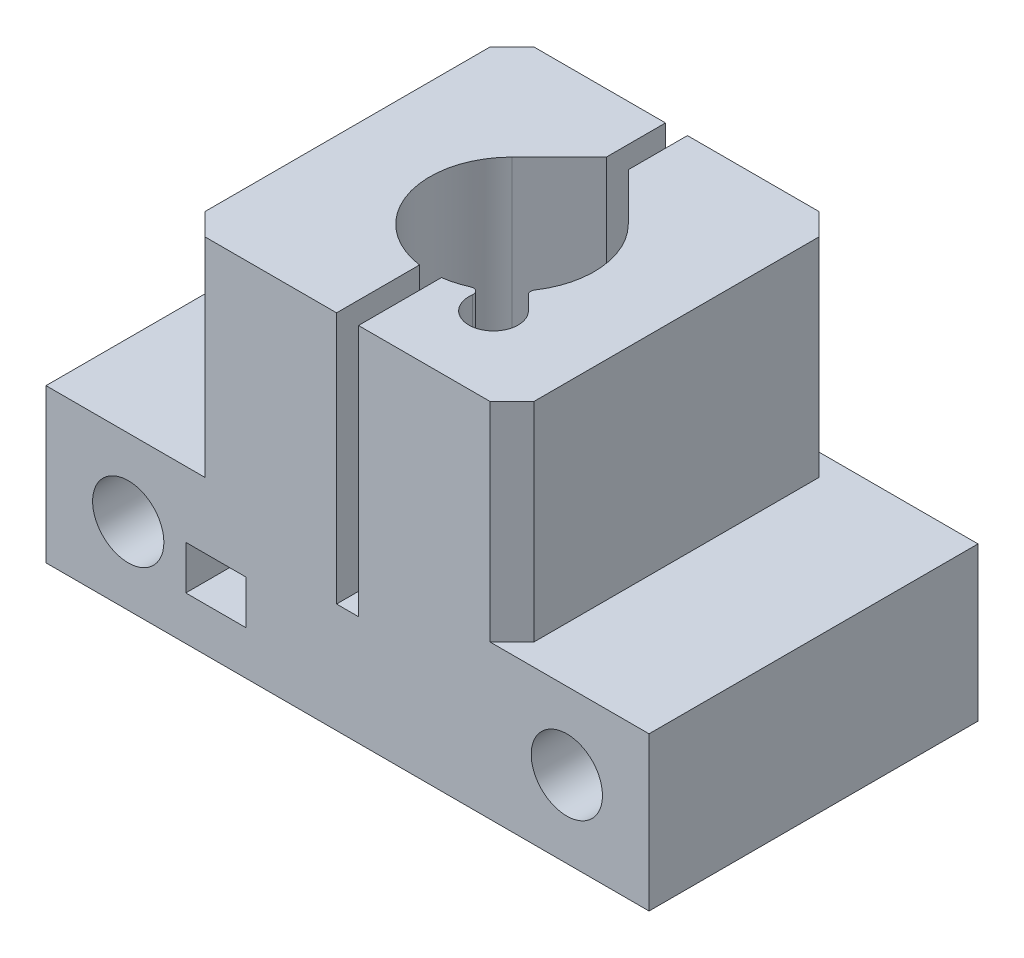
SolidWorks part; units mm, degrees
material "Printed PLA"
ref_plane "Front Plane" through (0, 0, 0) normal (0, 0, 1) x (1, 0, 0)
ref_plane "Top Plane" through (0, 0, 0) normal (0, 1, 0) x (1, 0, 0)
ref_plane "Right Plane" through (0, 0, 0) normal (1, 0, 0) x (0, 0, -1)
sketch "Sketch1" plane through (0, 0, 0) normal (0, 0, 1) x (1, 0, 0)
  line L0 (-27.5, 0) -> (27.5, 0)
  line L1 (27.5, 0) -> (27.5, 14)
  line L2 (27.5, 14) -> (15, 14)
  line L3 (15, 14) -> (15, 33)
  line L4 (15, 33) -> (1, 33)
  line L5 (1, 33) -> (1, 10)
  line L6 (1, 10) -> (-1, 10)
  line L7 (-1, 10) -> (-1, 33)
  line L8 (-1, 33) -> (-15, 33)
  line L9 (-15, 33) -> (-15, 14)
  line L10 (-15, 14) -> (-27.5, 14)
  line L11 (-27.5, 14) -> (-27.5, 0)
  line L12 (0, 10) -> (0, 0) construction
  line L13 (-27.5, 7) -> (-20, 7) construction
  line L14 (-20, 7) -> (20, 7) construction
  line L15 (20, 7) -> (27.5, 7) construction
  circle A0 centre (-20, 7) radius 3.25
  circle A1 centre (20, 7) radius 3.25
  dimension "D8" = 6.5
  dimension "D1" = 2
  dimension "D2" = 30
  dimension "D3" = 10
  dimension "D4" = 33
  dimension "D5" = 55
  dimension "D6" = 14
  dimension "D7" = 40
extrude "Boss-Extrude1" add sketch "Sketch1" along normal mid plane 30
sketch "Sketch2" plane through (0, 33, 0) normal (0, 1, 0) x (1, 0, 0)
  line L0 (-3.5355, 3.5355) -> (0, 7.0711)
  line L1 (0, 7.0711) -> (3.5355, 3.5355)
  line L3 (0, 7.0711) -> (0, 0) construction
  arc A0 (-3.5355, 3.5355) -> (3.5355, 3.5355) centre (0, 0) ccw
  dimension "D1" = 5
extrude "Cut-Extrude1" cut sketch "Sketch2" against normal through all
sketch "Sketch3" plane through (0, 33, 0) normal (0, 1, 0) x (1, 0, 0)
  line L0 (-5.3033, 5.3033) -> (0, 10.6066)
  line L1 (0, 10.6066) -> (5.3033, 5.3033)
  line L2 (0, 10.6066) -> (0, 0) construction
  arc A0 (-5.3033, 5.3033) -> (5.3033, 5.3033) centre (0, 0) ccw
  dimension "D1" = 7.5
extrude "Cut-Extrude2" cut sketch "Sketch3" against normal blind 24
chamfer "Chamfer1" distance 2 angle 45 4 edges at (-15, 23.5, -15) (-15, 23.5, 15) (15, 23.5, 15) (15, 23.5, -15)
sketch "Sketch6" plane through (0, 0, 0) normal (0, -1, 0) x (-1, 0, 0)
  line L0 (12, 9.5) -> (12, -9.5) construction
  line L1 (13.2374, -8.2626) -> (12, -7.0251)
  line L2 (12, -7.0251) -> (10.7626, -8.2626)
  line L3 (13.2374, 10.7374) -> (12, 11.9749)
  line L4 (12, 11.9749) -> (10.7626, 10.7374)
  line L5 (12, 0) -> (0, 0) construction
  arc A0 (10.7626, -8.2626) -> (13.2374, -8.2626) centre (12, -9.5) ccw
  arc A1 (10.7626, 10.7374) -> (13.2374, 10.7374) centre (12, 9.5) ccw
  dimension "D1" = 3.5
  dimension "D2" = 19
  dimension "D3" = 12
extrude "Cut-Extrude4" cut sketch "Sketch6" against normal blind 20
sketch "Sketch7" plane through (0, 0, 15) normal (0, 0, 1) x (1, 0, 0)
  line L0 (-12, 4) -> (-12, 0) construction
  line L1 (-14.75, 8) -> (-9.25, 8)
  line L2 (-14.75, 8) -> (-14.75, 4)
  line L3 (-14.75, 4) -> (-9.25, 4)
  line L4 (-9.25, 8) -> (-9.25, 4)
  line L5 (-27.5, 0) -> (27.5, 0) construction
  line L6 (-12, 20) -> (-12, 0) construction
  dimension "D1" = 5.5
  dimension "D2" = 4
  dimension "D3" = 4
extrude "Cut-Extrude5" cut sketch "Sketch7" against normal through all
sketch "Sketch8" plane through (0, 33, 0) normal (0, 1, 0) x (1, 0, 0)
  line L0 (0, 0) -> (6, -7.6852) construction
  line L1 (4.513, -5.9902) -> (5.9902, -4.513)
  line L2 (6.2969, -4.8001) -> (7.591, -6.0942)
  line L3 (6, -4.5032) -> (6, -7.6852) construction
  line L4 (1, -15) -> (1, -7.433) construction
  line L5 (3.0726, -6.8417) -> (4.513, -5.9902)
  line L6 (5.9902, -4.513) -> (6.2348, -4.1686)
  line L7 (5.9902, -4.513) -> (6, -4.5032) construction
  line L8 (6, -4.5032) -> (6.2969, -4.8001) construction
  arc A0 (3.7724, -7.3683) -> (7.591, -6.0942) centre (6, -7.6852) ccw
  arc A1 (1, -7.433) -> (5.3033, 5.3033) centre (0, 0) ccw construction
  arc A3 (3.0726, -6.8417) -> (3.7724, -7.3683) centre (3.2774, -7.2978) cw
  arc A4 (-5.3033, 5.3033) -> (5.3033, 5.3033) centre (0, 0) ccw construction
  arc A5 (6.2348, -4.1686) -> (6.2969, -4.8001) centre (6.6504, -4.4466) ccw
  dimension "D1" = 4.5
  dimension "D3" = 0.5
  dimension "D2" = 5
extrude "Cut-Extrude6" cut sketch "Sketch8" against normal up to surface (24 mm away) up to face at (0, 9, -2.8033)
sketch "Sketch9" plane through (0, 33, 0) normal (0, 1, 0) x (1, 0, 0)
  line L0 (4.409, -6.0942) -> (6, -4.5032)
  line L1 (6, -4.5032) -> (7.591, -6.0942)
  line L2 (6, -4.5032) -> (6, -7.6852) construction
  arc A0 (4.409, -6.0942) -> (7.591, -6.0942) centre (6, -7.6852) ccw
extrude "Cut-Extrude7" cut sketch "Sketch9" against normal through all
